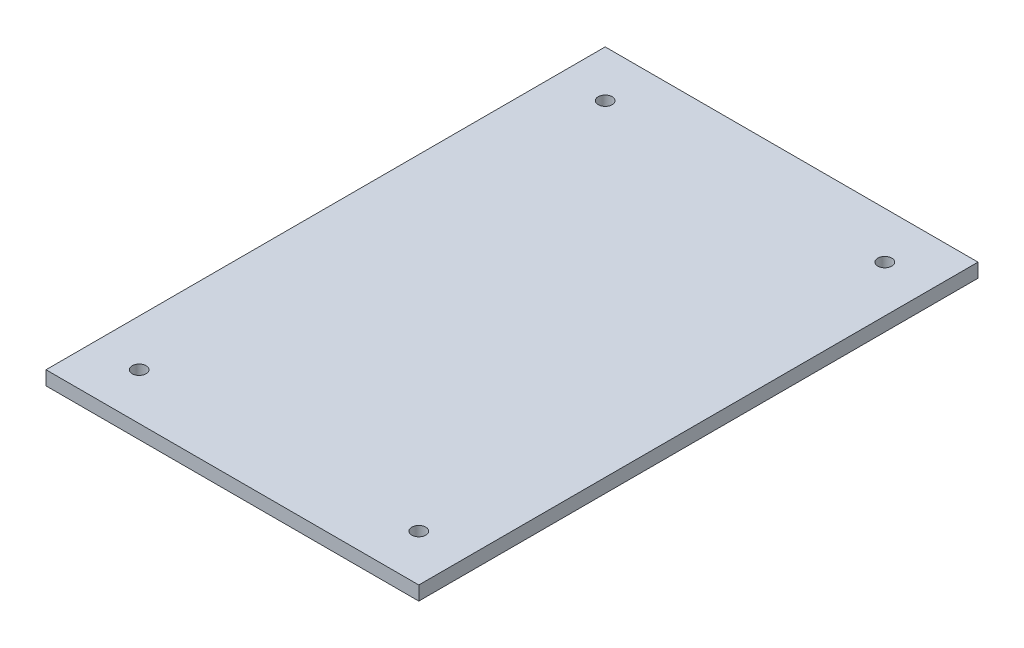
SolidWorks part; units mm, degrees
material "Acrylic (Medium-high impact)"
ref_plane "Front Plane" through (0, 0, 0) normal (0, 0, 1) x (1, 0, 0)
ref_plane "Top Plane" through (0, 0, 0) normal (0, 1, 0) x (1, 0, 0)
ref_plane "Right Plane" through (0, 0, 0) normal (1, 0, 0) x (0, 0, -1)
sketch "Sketch1" plane through (0, 0, 0) normal (0, 1, 0) x (1, 0, 0)
  line L1 (40, -60) -> (-40, -60)
  line L2 (40, -60) -> (40, 60)
  line L3 (40, 60) -> (-40, 60)
  line L4 (-40, -60) -> (-40, 60)
  line L5 (40, -60) -> (-40, 60) construction
  line L6 (40, 60) -> (-40, -60) construction
  point P0 (0, 0)
  dimension "D1" = 120
  dimension "D2" = 80
extrude "Boss-Extrude1" add sketch "Sketch1" along normal blind 3
sketch "Sketch3" plane through (0, 3, 0) normal (0, 1, 0) x (1, 0, 0)
  line L0 (-40, -60) -> (40, -60) construction
  line L1 (-40, 60) -> (-40, -60) construction
  line L2 (0, -60) -> (0, 0) construction
  line L3 (0, 0) -> (-40, 0) construction
  circle A0 centre (-30, -50) radius 1.5
  circle A1 centre (30, -50) radius 1.5
  circle A2 centre (30, 50) radius 1.5
  circle A3 centre (-30, 50) radius 1.5
  dimension "D1" = 3
  dimension "D2" = 10
  dimension "D3" = 10
extrude "Cut-Extrude2" cut sketch "Sketch3" against normal blind 3
